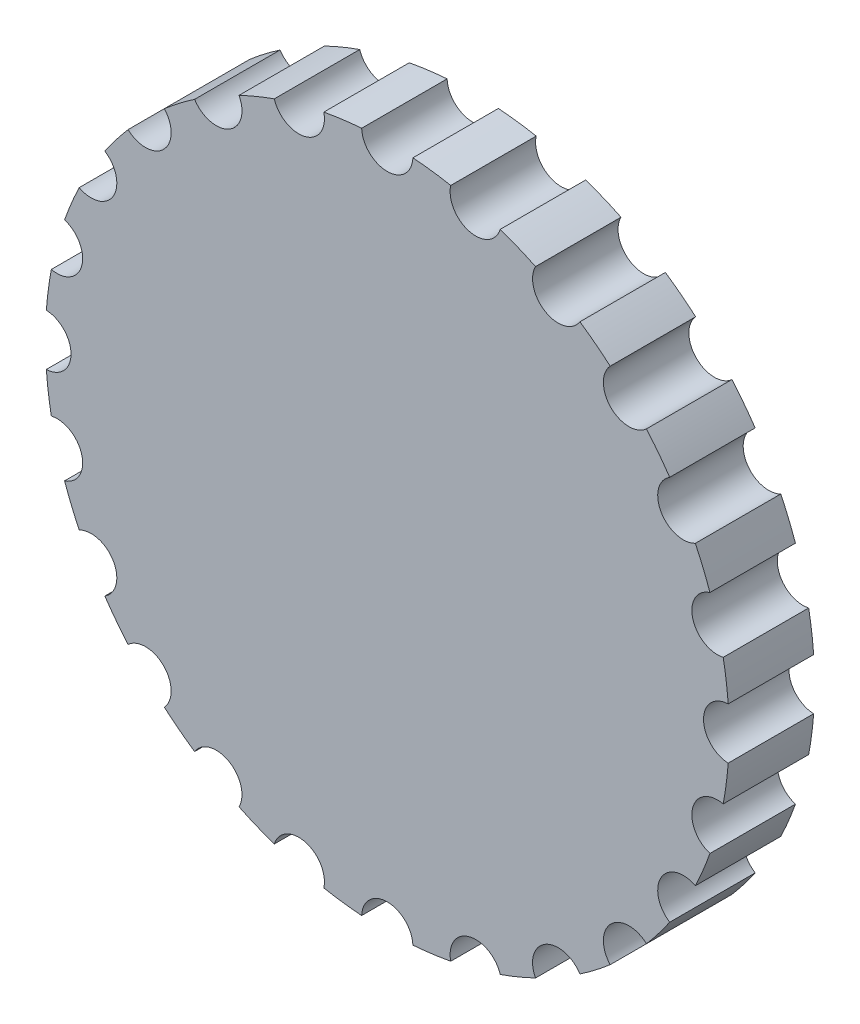
SolidWorks part; units mm, degrees
ref_plane "Front Plane" through (0, 0, 0) normal (0, 0, 1) x (1, 0, 0)
ref_plane "Top Plane" through (0, 0, 0) normal (0, 1, 0) x (1, 0, 0)
ref_plane "Right Plane" through (0, 0, 0) normal (1, 0, 0) x (0, 0, -1)
sketch "Sketch1" plane through (0, 0, 0) normal (0, 0, 1) x (1, 0, 0)
  circle A0 centre (0, 0) radius 20
  dimension "D1" = 40
extrude "Boss-Extrude1" add sketch "Sketch1" along normal blind 5
sketch "Sketch3" plane through (0, 0, 5) normal (0, 0, 1) x (1, 0, 0)
  circle A0 centre (0, 20) radius 1.5
  circle A1 centre (0, 0) radius 20 construction
  circle A2 centre (5.1764, 19.3185) radius 1.5
  circle A3 centre (10, 17.3205) radius 1.5
  circle A4 centre (14.1421, 14.1421) radius 1.5
  circle A5 centre (17.3205, 10) radius 1.5
  circle A6 centre (19.3185, 5.1764) radius 1.5
  circle A7 centre (20, 0) radius 1.5
  circle A8 centre (19.3185, -5.1764) radius 1.5
  circle A9 centre (17.3205, -10) radius 1.5
  circle A10 centre (14.1421, -14.1421) radius 1.5
  circle A11 centre (10, -17.3205) radius 1.5
  circle A12 centre (5.1764, -19.3185) radius 1.5
  circle A13 centre (0, -20) radius 1.5
  circle A14 centre (-5.1764, -19.3185) radius 1.5
  circle A15 centre (-10, -17.3205) radius 1.5
  circle A16 centre (-14.1421, -14.1421) radius 1.5
  circle A17 centre (-17.3205, -10) radius 1.5
  circle A18 centre (-19.3185, -5.1764) radius 1.5
  circle A19 centre (-20, 0) radius 1.5
  circle A20 centre (-19.3185, 5.1764) radius 1.5
  circle A21 centre (-17.3205, 10) radius 1.5
  circle A22 centre (-14.1421, 14.1421) radius 1.5
  circle A23 centre (-10, 17.3205) radius 1.5
  circle A24 centre (-5.1764, 19.3185) radius 1.5
  point P25 (0, 0)
  dimension "D1" = 3
  dimension "D2" = 24
extrude "Cut-Extrude1" cut sketch "Sketch3" along direction (0, 0, 1) on the side against the normal up to surface (5 mm away)
